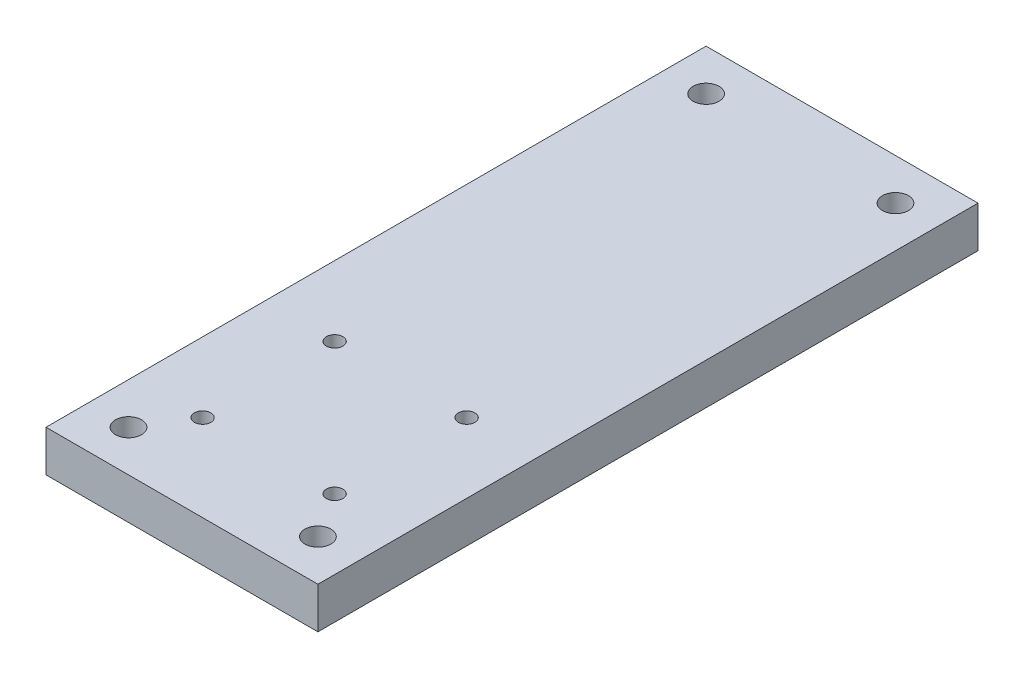
SolidWorks part; units mm, degrees
material "ABS PC"
ref_plane "Front Plane" through (0, 0, 0) normal (0, 0, 1) x (1, 0, 0)
ref_plane "Top Plane" through (0, 0, 0) normal (0, 1, 0) x (1, 0, 0)
ref_plane "Right Plane" through (0, 0, 0) normal (1, 0, 0) x (0, 0, -1)
sketch "Sketch1" plane through (0, 0, 0) normal (0, 1, 0) x (1, 0, 0)
  line L1 (0, 0) -> (20, 0)
  line L2 (0, 0) -> (0, 40)
  line L3 (0, 40) -> (20, 40)
  line L4 (20, 0) -> (20, 40)
  dimension "D1" = 40
  dimension "D2" = 20
extrude "Boss-Extrude1" add sketch "Sketch1" along normal blind 5
sketch "Sketch2" plane through (0, 0, 0) normal (0, -1, 0) x (1, 0, 0)
  line L0 (0, 0) -> (20, 0) construction
  line L3 (0, -40) -> (0, 0) construction
  circle A0 centre (2.158, -12) radius 1
  circle A1 centre (18.158, -12) radius 1
  circle A2 centre (18.158, -28) radius 1
  circle A3 centre (2.158, -28) radius 1
  dimension "D1" = 2
  dimension "D2" = 16
  dimension "D3" = 16
  dimension "D4" = 16
  dimension "D5" = 12
  dimension "2mm" = 2.158
sketch "Sketch3" plane through (0, 0, -40) normal (0, 0, -1) x (-1, 0, 0)
  line L4 (-20, 0) -> (0, 0)
  line L5 (0, 0) -> (0, 5)
  line L6 (0, 5) -> (-20, 5)
  line L7 (-20, 5) -> (-20, 0)
  line L8 (-20, 0) -> (0, 0)
  line L9 (0, 0) -> (0, 5)
  line L10 (0, 5) -> (-20, 5)
  line L11 (-20, 5) -> (-20, 0)
  dimension "D1" = 0
extrude "Boss-Extrude2" add sketch "Sketch3" along normal blind 33
sketch "Sketch4" plane through (0, 5, 0) normal (0, 1, 0) x (1, 0, 0)
  line L0 (0, 73) -> (0, 0) construction
  line L1 (0, 3) -> (20, 3)
  line L2 (0, 3) -> (0, 0)
  line L3 (0, 0) -> (20, 0)
  line L4 (20, 3) -> (20, 0)
  dimension "D1" = 3
extrude "Cut-Extrude2" cut sketch "Sketch4" against normal through all
sketch "Sketch5" plane through (0, 0, -73) normal (0, 0, -1) x (-1, 0, 0)
  line L1 (-20, 5) -> (0, 5)
  line L2 (-20, 5) -> (-20, 0)
  line L3 (-20, 0) -> (0, 0)
  line L4 (0, 5) -> (0, 0)
extrude "Boss-Extrude3" add sketch "Sketch5" along normal blind 10
sketch "Sketch6" plane through (0, 0, -83) normal (0, 0, -1) x (-1, 0, 0)
  line L4 (-20, 5) -> (-20, 0)
  line L5 (-20, 0) -> (0, 0)
  line L6 (0, 0) -> (0, 5)
  line L7 (0, 5) -> (-20, 5)
  line L8 (-20, 5) -> (-20, 0)
  line L9 (-20, 0) -> (0, 0)
  line L10 (0, 0) -> (0, 5)
  line L11 (0, 5) -> (-20, 5)
  dimension "D1" = 0
extrude "Boss-Extrude4" add sketch "Sketch6" along normal blind 1.5
sketch "Sketch7" plane through (0, 0, -3) normal (0, 0, 1) x (1, 0, 0)
  line L4 (20, 5) -> (0, 5)
  line L5 (0, 5) -> (0, 0)
  line L6 (0, 0) -> (20, 0)
  line L7 (20, 0) -> (20, 5)
  line L8 (20, 5) -> (0, 5)
  line L9 (0, 5) -> (0, 0)
  line L10 (0, 0) -> (20, 0)
  line L11 (20, 0) -> (20, 5)
  dimension "D1" = 0
extrude "Boss-Extrude5" add sketch "Sketch7" along normal blind 1.5
sketch "Sketch9" plane through (0, 0, 0) normal (-1, 0, 0) x (0, 0, 1)
  line L4 (-84.5, 0) -> (-1.5, 0)
  line L5 (-1.5, 0) -> (-1.5, 5)
  line L6 (-1.5, 5) -> (-84.5, 5)
  line L7 (-84.5, 5) -> (-84.5, 0)
  line L8 (-84.5, 0) -> (-1.5, 0)
  line L9 (-1.5, 0) -> (-1.5, 5)
  line L10 (-1.5, 5) -> (-84.5, 5)
  line L11 (-84.5, 5) -> (-84.5, 0)
  dimension "D1" = 0
extrude "Boss-Extrude7" add sketch "Sketch9" along normal blind 12.954
sketch "Sketch10" plane through (0, 0, 0) normal (0, -1, 0) x (1, 0, 0)
  line L0 (-12.954, -1.5) -> (20, -1.5) construction
  line L1 (3.523, -1.5) -> (3.523, -37.2579) construction
  circle A0 centre (-4.477, -13.5) radius 1
  circle A1 centre (11.523, -13.5) radius 1
  circle A2 centre (11.523, -29.5) radius 1
  circle A3 centre (-4.477, -29.5) radius 1
  dimension "D1" = 2
  dimension "D2" = 16
  dimension "D3" = 16
  dimension "D4" = 16
  dimension "D5" = 8
  dimension "D6" = 8
  dimension "D7" = 12
extrude "Cut-Extrude3" cut sketch "Sketch10" against normal through all
sketch "Sketch11" plane through (0, 0, 0) normal (0, -1, 0) x (1, 0, 0)
  line L0 (20, -1.5) -> (20, -84.5) construction
  line L1 (-12.954, -1.5) -> (20, -1.5)
  line L2 (-12.954, -1.5) -> (-12.954, -2.9986)
  line L3 (-12.954, -2.9986) -> (20, -2.9986)
  line L4 (20, -1.5) -> (20, -2.9986)
  line L6 (-12.954, -84.5) -> (20, -84.5)
  line L7 (-12.954, -84.5) -> (-12.954, -82.9963)
  line L8 (-12.954, -82.9963) -> (20, -82.9963)
  line L9 (20, -84.5) -> (20, -82.9963)
  dimension "D1" = 1.4986
  dimension "D2" = 1.5037
extrude "Cut-Extrude4" cut sketch "Sketch11" against normal through all
sketch "Sketch12" plane through (0, 0, 0) normal (0, -1, 0) x (1, 0, 0)
  line L0 (-12.954, -2.9986) -> (20, -2.9986) construction
  line L1 (-12.954, -82.9963) -> (-12.954, -2.9986) construction
  line L2 (20, -2.9986) -> (20, -82.9963) construction
  line L3 (20, -82.9963) -> (-12.954, -82.9963) construction
  circle A0 centre (-7.954, -7.9986) radius 1.575
  circle A1 centre (15, -7.9986) radius 1.575
  circle A2 centre (15, -77.9963) radius 1.575
  circle A3 centre (-7.954, -77.9963) radius 1.575
  dimension "D1" = 3.15
  dimension "D2" = 5
  dimension "D3" = 5
  dimension "D4" = 5
  dimension "D5" = 5
extrude "Cut-Extrude5" cut sketch "Sketch12" against normal through all
